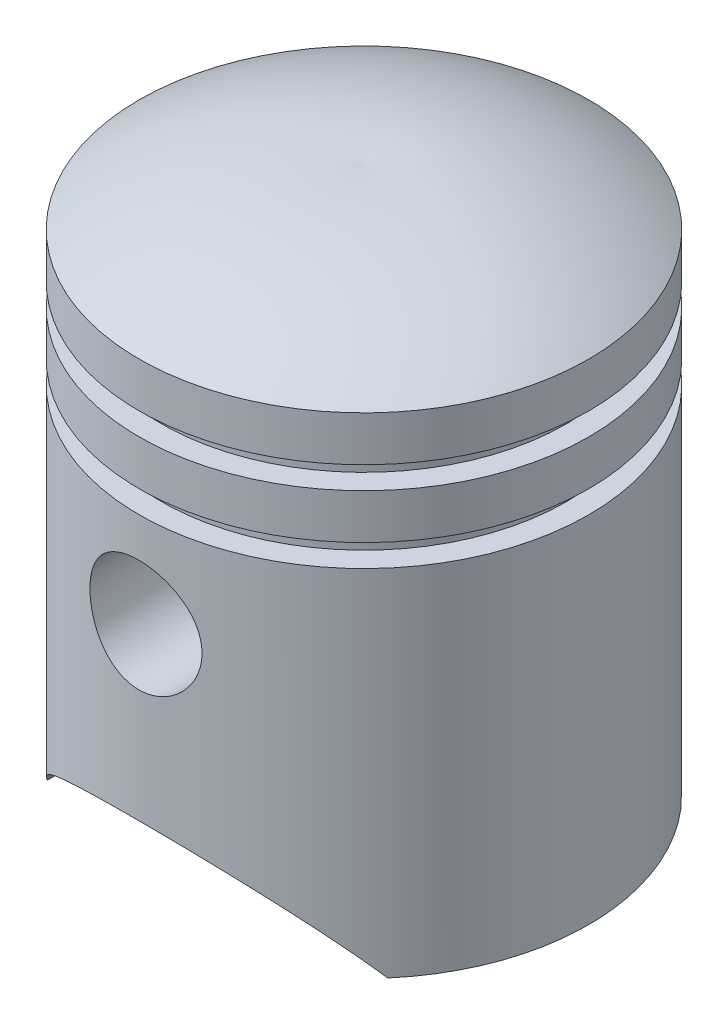
SolidWorks part; units mm, degrees
ref_plane "Front Plane" through (0, 0, 0) normal (0, 0, 1) x (1, 0, 0)
ref_plane "Top Plane" through (0, 0, 0) normal (0, 1, 0) x (1, 0, 0)
ref_plane "Right Plane" through (0, 0, 0) normal (1, 0, 0) x (0, 0, -1)
sketch "Sketch1" plane through (0, 0, 0) normal (0, 0, 1) x (1, 0, 0)
  line L0 (25.0486, 0) -> (25.0486, 39.5)
  line L1 (25.0486, 49.5) -> (25.0486, 54.5)
  line L2 (25.0486, 49.5) -> (22.5486, 49.5)
  line L4 (25.0486, 47) -> (22.5486, 47)
  line L5 (22.5486, 49.5) -> (22.5486, 47)
  line L6 (25.0486, 42) -> (22.5486, 42)
  line L8 (25.0486, 39.5) -> (22.5486, 39.5)
  line L9 (22.5486, 42) -> (22.5486, 39.5)
  line L10 (25.0486, 42) -> (25.0486, 47)
  line L11 (23.0486, 0) -> (23.0486, 37.5)
  line L12 (23.0486, 37.5) -> (20.5486, 37.5)
  line L13 (20.5486, 44) -> (20.5486, 37.5)
  line L14 (23.0486, 44) -> (20.5486, 44)
  line L15 (23.0486, 44) -> (23.0486, 45)
  line L16 (23.0486, 45) -> (20.5486, 45)
  line L17 (20.5486, 51.5) -> (20.5486, 45)
  line L18 (23.0486, 51.5) -> (20.5486, 51.5)
  line L19 (23.0486, 51.5) -> (23.0486, 53.3979)
  line L21 (23.0486, 0) -> (23.0486, 37.5) construction
  line L22 (25.0486, 0) -> (25.0486, 39.5) construction
  line L23 (25.0486, 0) -> (23.0486, 0)
  line L24 (0.0486, 60.8613) -> (0.0486, 58.8547)
  arc A0 (25.0486, 54.5) -> (0.0486, 60.8613) centre (3.2118, 20.9866) ccw
  arc A1 (23.0486, 53.3979) -> (0.0486, 58.8547) centre (3.2118, 20.9866) ccw
  arc A2 (23.0486, 53.3979) -> (0.2068, 58.8676) centre (3.2118, 20.9866) ccw construction
  point P24 (0, 0)
  point P27 (0, 0)
  point P28 (0, 0)
  point P29 (0, 0)
  point P30 (0, 0)
  point P31 (0, 0)
  point P32 (0, 0)
  point P33 (0, 0)
  point P34 (0, 0)
  point P35 (0, 0)
  point P36 (0, 0)
  point P37 (0, 0)
  point P38 (1.2634, 58.6069)
  point P41 (0.0486, 58.7577)
  dimension "D4" = 40
  dimension "D2" = 25
  dimension "D5" = 5
  dimension "D6" = 5
  dimension "D7" = 2.5
  dimension "D8" = 2.5
  dimension "D9" = 2.5
  dimension "D10" = 2.5
  dimension "D11" = 2
revolve "Revolve4" add sketch "Sketch1" angle 360 about L24
sketch "Sketch4" plane through (0, 0, 0) normal (0, 0, 1) x (1, 0, 0)
  line L0 (-24.9514, 0) -> (25.0486, 0) construction
  line L1 (-19, 0) -> (19, 0)
  circle A0 centre (0, 28.8613) radius 6.25
  arc A1 (-19, 0) -> (19, 0) centre (0, -13.05) cw
  point P12 (0, 10)
  dimension "D1" = 12.5
  dimension "D3" = 10
  dimension "D2" = 32
  dimension "D4" = 38
extrude "Cut-Extrude3" cut sketch "Sketch4" against normal mid plane 64
sketch "Sketch9" plane through (0, 0, 0) normal (0, 0, 1) x (1, 0, 0)
  circle A0 centre (0, 28.8613) radius 6.25
  circle A1 centre (0, 28.8613) radius 7.25
  dimension "D1" = 14.5
extrude "Boss-Extrude7" add sketch "Sketch9" along normal up to surface (12.2187 mm away) from offset 12
mirror "Mirror2" about plane through (0, 0, 0) normal (0, 0, 1) of "Boss-Extrude7"
